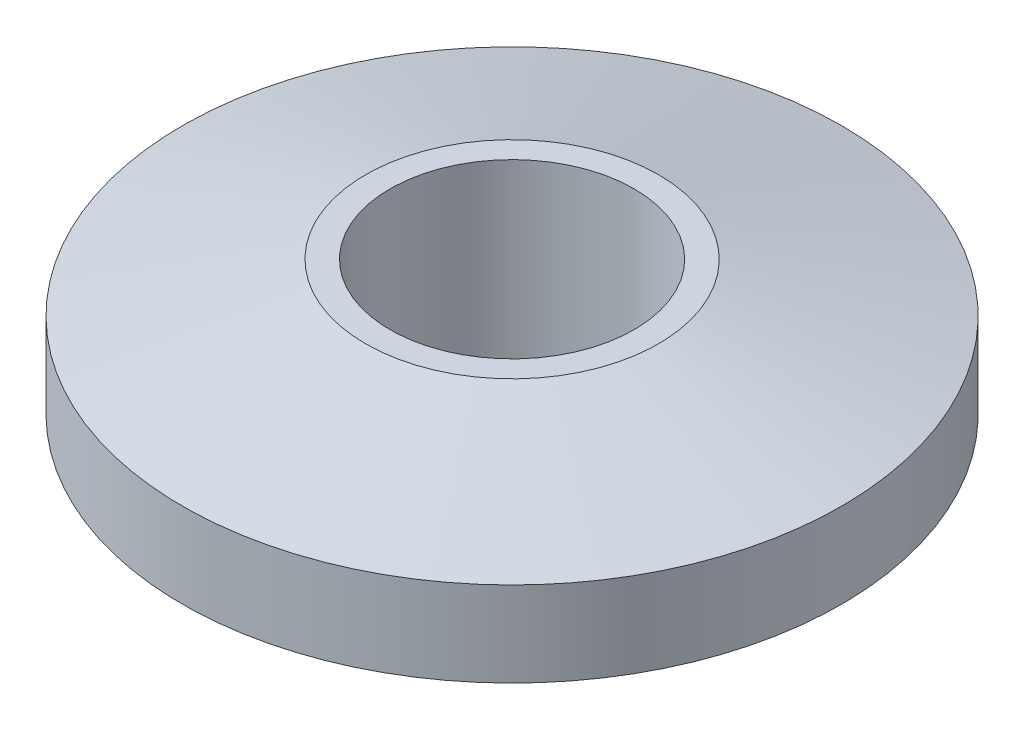
SolidWorks part; units mm, degrees
ref_plane "前视基准面" through (0, 0, 0) normal (0, 0, 1) x (1, 0, 0)
ref_plane "上视基准面" through (0, 0, 0) normal (0, 1, 0) x (1, 0, 0)
ref_plane "右视基准面" through (0, 0, 0) normal (1, 0, 0) x (0, 0, -1)
sketch "草图1" plane through (0, 0, 0) normal (0, 0, 1) x (1, 0, 0)
  line L0 (0, 0) -> (0, 63.3409) construction
  line L1 (0, -55) -> (0, 55) construction
  line L2 (-13.5, -1.7404) -> (-13.5, 1.7404)
  line L3 (55, 0) -> (-55, 0) construction
  line L4 (-13.5, 1.7404) -> (-6, 3.75)
  line L5 (-5, 0) -> (-47.6746, 0) construction
  line L6 (-13.5, -1.7404) -> (-6, -3.75)
  line L8 (-6, 3.75) -> (0, 5.3577) construction
  line L9 (0, 0) -> (-5, 0) construction
  line L10 (-6, -3.75) -> (0, -5.3577) construction
  line L11 (-6, 3.75) -> (-5, 3.75)
  line L12 (-5, 3.75) -> (-5, -3.75)
  line L13 (-5, -3.75) -> (-6, -3.75)
  point P12 (-13.5, 0)
  point P16 (-13.5, -1.8043)
  dimension "D1" = 30
  dimension "D2" = 12
  dimension "D3" = 27
  dimension "D4" = 7.5
  dimension "D5" = 10
revolve "旋转1" add sketch "草图1" angle 360 about L0
